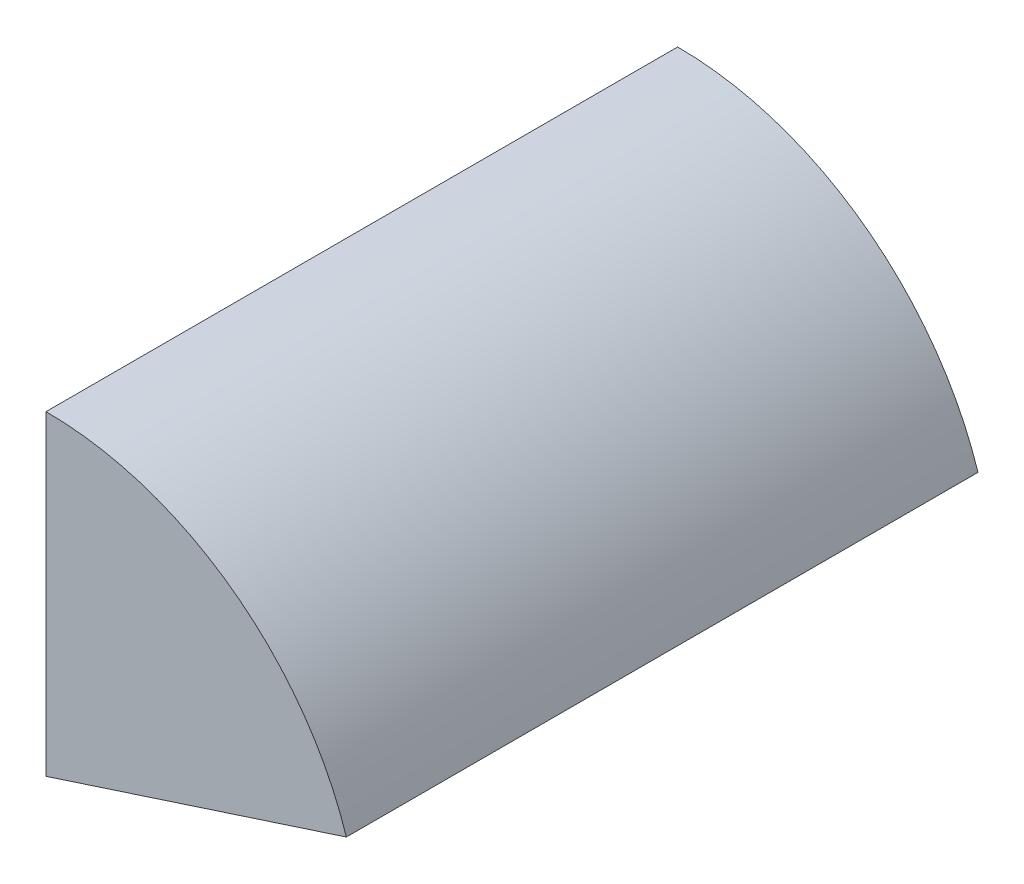
SolidWorks part; units mm, degrees
ref_plane "Alzado" through (0, 0, 0) normal (0, 0, 1) x (1, 0, 0)
ref_plane "Planta" through (0, 0, 0) normal (0, 1, 0) x (1, 0, 0)
ref_plane "Vista lateral" through (0, 0, 0) normal (1, 0, 0) x (0, 0, -1)
sketch "Croquis1" plane through (0, 0, 0) normal (0, 0, 1) x (1, 0, 0)
  line L0 (0, 25) -> (0, 0)
  line L1 (0, 0) -> (23.7764, 7.7254)
  arc A0 (23.7764, 7.7254) -> (0, 25) centre (0, 0) ccw
  dimension "D1" = 50
  dimension "D2" = 72
extrude "Saliente-Extruir1" add sketch "Croquis1" along normal blind 50
sketch "Croquis2" plane through (0, 0, 0) normal (0, 0, -1) x (-1, 0, 0)
  circle A0 centre (-8.7308, 12.2908) radius 5
  dimension "D1" = 10
extrude "Cortar-Extruir1" cut sketch "Croquis2" against normal blind 10
